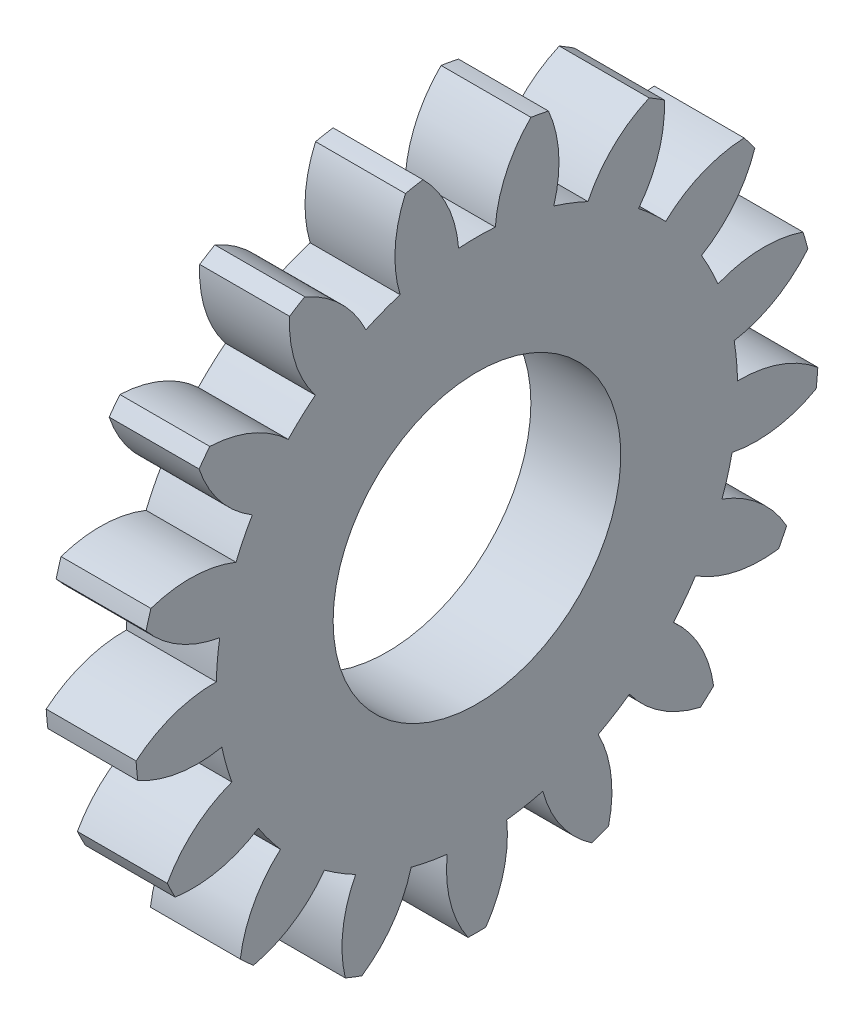
SolidWorks part; units mm, degrees
ref_plane "Plane1" through (0, 0, 0) normal (0, 0, 1) x (1, 0, 0)
ref_plane "Plane2" through (0, 0, 0) normal (0, 1, 0) x (1, 0, 0)
ref_plane "Plane3" through (0, 0, 0) normal (1, 0, 0) x (0, 0, -1)
other "Configuration Table"
sketch "HoldingSke" plane through (0, 0, 0) normal (0, 1, 0) x (1, 0, 0)
  line L0 (0, 0) -> (0.4782, -0.1462)
  line L1 (-15, 0) -> (100, 0) construction
  line L2 (0, 0) -> (-2.1039, 2.3779)
  line L3 (0, 0) -> (-11.863, 4.5341)
  line L4 (0, 0) -> (8.2586, 2.5249)
  line L5 (0, 0) -> (-46.8476, -17.4728)
  line L6 (0, 0) -> (-4.1448, -2.7965)
  line L7 (-2.1039, 2.3779) -> (8.6586, 51.2059)
  line L8 (-76.2, 54.61) -> (-73.9, 54.61)
  line L9 (-71.009, 38.7566) -> (-53.1078, 45.2721)
  line L10 (-76.2, 71.12) -> (104.1128, 71.12)
  line L11 (0, 0) -> (-5, 0)
  line L12 (-76.2, 101.6) -> (-76.133, 101.6)
  line L13 (24.9733, 27.94) -> (52.9518, 28.4284)
  line L14 (24.9733, 27.94) -> (24.9743, 27.94)
  line L15 (24.9733, 27.94) -> (100.4006, 29.5858)
  line L16 (-63.627, -2) -> (-12.827, -2)
  circle A0 centre (0, 0) radius 8
  circle A1 centre (0, 0) radius 14.499
  circle A2 centre (0, 0) radius 37.5
  circle A3 centre (0, 0) radius 8
  dimension "MHD" = 28.998
  dimension "Hub_dia" = 75
  dimension "Bore" = 16
  dimension "MBD" = 16
  dimension "Num_teeth" = 17
  dimension "Pitch" = 0.5
  dimension "Overall_len" = 50
  dimension "Show_teeth" = 17
  dimension "Thickness" = 5
  dimension "OAL" = 50.0001
  dimension "T_dim" = 2.3
  dimension "Ap" = 20
  dimension "H" = 19.05
  dimension "Pitch_radius" = 180.3128
  dimension "Width" = 5
  dimension "Backlash" = 0.067
  dimension "Addendum_fac" = 1
  dimension "Dedendum_fac" = 1.25
  dimension "Clearance_fac" = 0.25
  dimension "Dedendum_add" = 0.001
  dimension "Module" = 2
sketch "BasProSke" plane through (0, 0, 0) normal (0, 1, 0) x (1, 0, 0)
  line L0 (-10, 0) -> (60, 0) construction
  line L1 (0, 0) -> (0, 19)
  line L2 (0, 0) -> (5, 0)
  line L3 (5, 0) -> (5, 19)
  line L4 (5, 19) -> (0, 19)
  dimension "Thickness" = 5
  dimension "Diameter" = 38
revolve "Base-Revolve" add sketch "BasProSke" angle 360 about L0
sketch "TooCutSke" plane through (0, 0, 0) normal (1, 0, 0) x (0, 0, -1)
  line L1 (0, 0) -> (0, 107) construction
  line L2 (0, 0) -> (-1.6857, 16.9162) construction
  line L3 (0, 0) -> (-6.2247, 33.2991) construction
  line L4 (-1.6857, 16.9162) -> (-3.1123, 16.6495) construction
  arc A0 (1.0204, 14.4631) -> (-1.0204, 14.4631) centre (0, 0) ccw
  arc A1 (3.0261, 18.7832) -> (-3.0261, 18.7832) centre (0, 0) ccw
  circle A2 centre (0, 0) radius 17 construction
  circle A3 centre (0, 0) radius 15.9748 construction
  arc A4 (-1.0204, 14.4631) -> (-3.0261, 18.7832) centre (-7.8003, 13.9409) ccw
  arc A5 (3.0261, 18.7832) -> (1.0204, 14.4631) centre (7.8003, 13.9409) ccw
  dimension "Root_dia" = 28.998
  dimension "Overcut_dia" = 38.0508
  dimension "Pitch_dia" = 34
  dimension "Base_dia" = 31.9495
  dimension "Flank_rad" = 6.8
  dimension "Half_ang" = 10.588
  dimension "Half_CT" = 1.4513
extrude "ToothCut" cut sketch "TooCutSke" along normal through all
fillet "Breaks" [suppressed] radius 0.04
fillet "RootFillets" [suppressed] radius 0.501
pattern_circular "TeethCuts" count 17 every 21.176 about axis through (-10, 0, 0) along (1, 0, 0) of "ToothCut", "RootFillets", "Breaks"
sketch "HubNeaOneSke" plane through (0, 0, 0) normal (-1, 0, 0) x (0, 0, 1)
  circle A0 centre (0, 0) radius 14.499
  dimension "Diameter" = 28.998
extrude "HubNearOne" [suppressed] add sketch "HubNeaOneSke" along normal blind 45.0001
sketch "HubNeaBotSke" plane through (0, 0, 0) normal (-1, 0, 0) x (0, 0, 1)
  circle A0 centre (0, 0) radius 14.499
  dimension "Diameter" = 28.998
extrude "HubNearBoth" [suppressed] add sketch "HubNeaBotSke" along normal blind 22.5
ref_plane "FarPln" through (5, 0, 0) normal (1, 0, 0) x (0, 0, -1)
sketch "HubFarSke" plane through (5, 0, 0) normal (1, 0, 0) x (0, 0, -1)
  circle A0 centre (0, 0) radius 14.499
  dimension "Diameter" = 28.998
extrude "HubFar" [suppressed] add sketch "HubFarSke" along normal blind 22.5
sketch "BorSke" plane through (0, 0, 0) normal (1, 0, 0) x (0, 0, -1)
  circle A0 centre (0, 0) radius 8
  dimension "Diameter" = 16
extrude "Bore" cut sketch "BorSke" along normal mid plane 100.0001
sketch "KeySke" plane through (0, 0, 0) normal (1, 0, 0) x (0, 0, -1)
  line L0 (-2.5, 0) -> (-2.5, 10.3)
  line L1 (-2.5, 10.3) -> (2.5, 10.3)
  line L2 (2.5, 10.3) -> (2.5, 0)
  line L3 (0, 0) -> (0, 34) construction
  line L4 (-2.5, 0) -> (2.5, 0)
  dimension "Width" = 5
  dimension "Offset" = 10.3
extrude "Keyway" [suppressed] cut sketch "KeySke" along normal mid plane 100.0001
pattern_circular "Keyway2" [suppressed] count 2 every 90 about axis through (-10, 0, 0) along (1, 0, 0)
sketch "草图1" plane through (5, 0, 0) normal (1, 0, 0) x (0, 0, -1)
  circle A0 centre (0, 0) radius 19
  circle A1 centre (0, 0) radius 17
  dimension "D1" = 34
equation "' \"Module@HoldingSke\" = 6.35"
equation "' \"Num_teeth@HoldingSke\" = 12"
equation "' \"Ap@HoldingSke\" =  20"
equation "' \"Ap@HoldingSke\" = 20"
equation "' \"Width@HoldingSke\" = 0.5 * 25.4"
equation "' \"Hub_dia@HoldingSke\"= 1 * 25.4"
equation "' \"Hub_dia@HoldingSke\" = 1 * 25.4"
equation "' \"Overall_len@HoldingSke\" = 1.0 * 25.4"
equation "' \"Bore@HoldingSke\" = 0.75 * 25.4"
equation "' \"T_dim@HoldingSke\" = 0.1 * 25.4"
equation "' \"Width@KeySke\" = 0.25 * 25.4"
equation "' \"Show_teeth@HoldingSke\" = 13"
equation "' \"Backlash@HoldingSke\" = 0.009 * 25.4"
equation "' \"Addendum_fac@HoldingSke\" = 1.0"
equation "' \"Dedendum_fac@HoldingSke\" = 1.25"
equation "' \"Dedendum_add@HoldingSke\" = 0.00005 * 25.4"
equation "' \"Clearance_fac@HoldingSke\" = 0.25"
equation "\"Pitch@HoldingSke\" = 1 / \"Module@HoldingSke\""
equation "\"Overcut_dia@TooCutSke\" = (\"Num_teeth@HoldingSke\" + 2 * \"Addendum_fac@HoldingSke\") / \"Pitch@HoldingSke\" + 0.002 * 25.4"
equation "\"Pitch_dia@TooCutSke\" = \"Num_teeth@HoldingSke\" / \"Pitch@HoldingSke\""
equation "\"Base_dia@TooCutSke\" = \"Num_teeth@HoldingSke\" / \"Pitch@HoldingSke\" * cos((\"Ap@HoldingSke\"  * 3.14159265 / 180))"
equation "\"Root_dia@TooCutSke\" = (\"Num_teeth@HoldingSke\" + 2) / \"Pitch@HoldingSke\" - 2 * (\"Addendum_fac@HoldingSke\" + \"Dedendum_fac@HoldingSke\") / \"Pitch@HoldingSke\" - \"Dedendum_add@HoldingSke\" * 2"
equation "\"Half_ang@TooCutSke\" = 180 / \"Num_teeth@HoldingSke\""
equation "\"Half_CT@TooCutSke\" = \"Num_teeth@HoldingSke\" / \"Pitch@HoldingSke\" * sin((3.14159265 / 2 / \"Num_teeth@HoldingSke\")) / 2 - 7 * \"Backlash@HoldingSke\" / 4"
equation "\"Flank_rad@TooCutSke\" = \"Num_teeth@HoldingSke\" / \"Pitch@HoldingSke\" / 5"
equation "\"Radius@RootFillets\" = \"Clearance_fac@HoldingSke\" / \"Pitch@HoldingSke\" + \"Dedendum_add@HoldingSke\""
equation "\"Break_rad@Breaks\" = 0.02 / \"Pitch@HoldingSke\""
equation "\"Thickness@HoldingSke\" = \"Width@HoldingSke\""
equation "\"OAL@HoldingSke\" = \"Thickness@HoldingSke\""
equation "\"MHD@HoldingSke\" = (\"Num_teeth@HoldingSke\" + 2) / \"Pitch@HoldingSke\" - 2 * (\"Addendum_fac@HoldingSke\" + \"Dedendum_fac@HoldingSke\")  / \"Pitch@HoldingSke\" - \"Dedendum_add@HoldingSke\" * 2"
equation "\"MBD@HoldingSke\" = (\"Num_teeth@HoldingSke\" + 2) / \"Pitch@HoldingSke\" - 2 * (\"Addendum_fac@HoldingSke\" + \"Dedendum_fac@HoldingSke\")  / \"Pitch@HoldingSke\" - \"Dedendum_add@HoldingSke\" * 2 - 0.002 * 25.4"
equation "\"MHD@HoldingSke\" = ((sgn( \"MHD@HoldingSke\" - \"Hub_dia@HoldingSke\" )-1)*( \"MHD@HoldingSke\" - \"Hub_dia@HoldingSke\" ))/-2+ \"Hub_dia@HoldingSke\""
equation "\"MBD@HoldingSke\" = ((sgn( \"MBD@HoldingSke\" - \"Bore@HoldingSke\" )-1)*( \"MBD@HoldingSke\" - \"Bore@HoldingSke\" ))/-2+ \"Bore@HoldingSke\""
equation "\"OAL@HoldingSke\" = ((sgn( \"OAL@HoldingSke\" - \"Overall_len@HoldingSke\" )+1)*( \"OAL@HoldingSke\" - \"Overall_len@HoldingSke\" ))/2 + \"Overall_len@HoldingSke\" + 0.000002 * 25.4"
equation "\"Num_teeth@TeethCuts\" = int( \"Show_teeth@HoldingSke\" ) + 1"
equation "\"Num_teeth@TeethCuts\" = ((sgn( \"Num_teeth@TeethCuts\" - \"Num_teeth@HoldingSke\" )-1)*( \"Num_teeth@TeethCuts\" - \"Num_teeth@HoldingSke\" ))/-2+ \"Num_teeth@HoldingSke\""
equation "\"Num_teeth@TeethCuts\" = ((sgn( \"Num_teeth@TeethCuts\" - 2.0)+1)*( \"Num_teeth@TeethCuts\" - 2.0))/2 +2.0"
equation "\"Angle@TeethCuts\" = 360.0 / \"Num_teeth@HoldingSke\""
equation "\"Diameter@BasProSke\" = (\"Num_teeth@HoldingSke\" + 2 * \"Addendum_fac@HoldingSke\") / \"Pitch@HoldingSke\""
equation "\"Thickness@BasProSke\"  = \"Thickness@HoldingSke\""
equation "' \"Fillet_rad@BasProSke\" =  \"Thickness@HoldingSke\" * 0.05"
equation "' \"Fillet_rad@BasProSke\" = \"Thickness@HoldingSke\" * 0.05"
equation "\"MHD@HoldingSke\" = ((sgn( \"MHD@HoldingSke\" - \"Root_dia@TooCutSke\" )-1)*( \"MHD@HoldingSke\" - \"Root_dia@TooCutSke\" ))/-2+ \"Root_dia@TooCutSke\""
equation "\"Diameter@HubNeaOneSke\" = \"MHD@HoldingSke\""
equation "\"Length@HubNearOne\" = \"OAL@HoldingSke\" - \"Thickness@BasProSke\""
equation "\"Diameter@HubNeaBotSke\" = \"MHD@HoldingSke\""
equation "\"Length@HubNearBoth\" = ( \"OAL@HoldingSke\" - \"Thickness@BasProSke\" ) / 2.0"
equation "\"Thickness@FarPln\" = \"Thickness@BasProSke\""
equation "\"Diameter@HubFarSke\" = \"MHD@HoldingSke\""
equation "\"Length@HubFar\" = ( \"OAL@HoldingSke\" - \"Thickness@BasProSke\" ) / 2.0"
equation "\"Diameter@BorSke\" = \"MBD@HoldingSke\""
equation "\"D1@Bore\" = \"OAL@HoldingSke\" * 2.0"
equation "\"D1@Keyway\" = \"OAL@HoldingSke\" * 2.0"
equation "\"Offset@KeySke\" = \"T_dim@HoldingSke\" + \"MBD@HoldingSke\" / 2.0"
